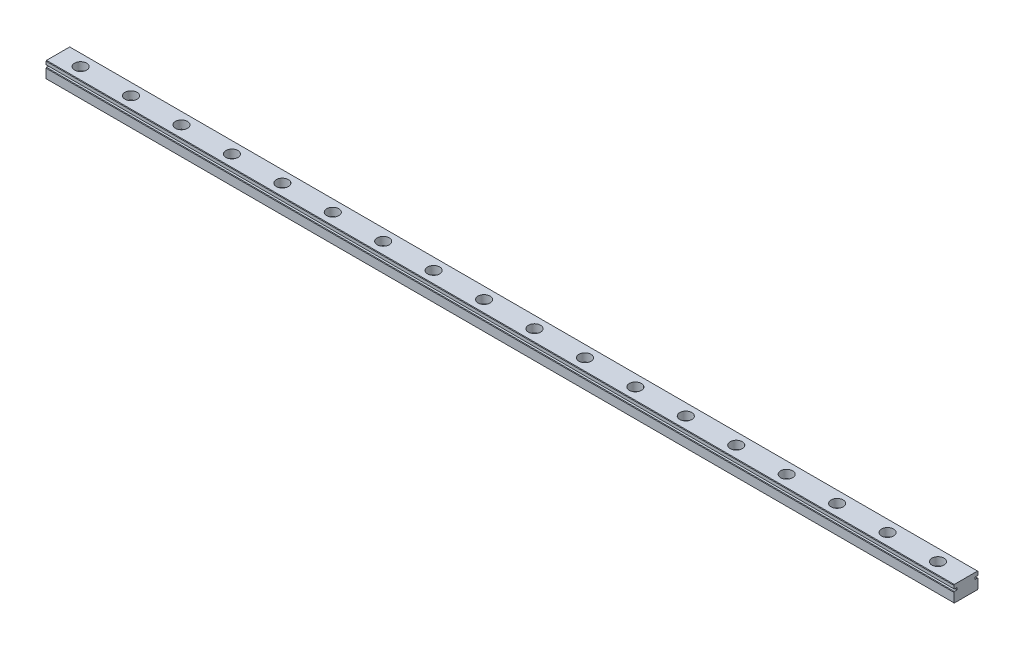
SolidWorks part; units mm, degrees
ref_plane "Plan de face" through (0, 0, 0) normal (0, 0, 1) x (1, 0, 0)
ref_plane "Plan de dessus" through (0, 0, 0) normal (0, 1, 0) x (1, 0, 0)
ref_plane "Plan de droite" through (0, 0, 0) normal (1, 0, 0) x (0, 0, -1)
sketch "Esquisse1" plane through (0, 0, 0) normal (1, 0, 0) x (0, 0, -1)
  line L0 (6, 5) -> (6, 0)
  line L1 (6, 8) -> (0, 8)
  line L2 (6, 8) -> (6, 6)
  line L3 (6, 0) -> (0, 0)
  line L5 (6, 6) -> (4.4, 6)
  line L7 (6, 5) -> (4.4, 5)
  line L8 (4.4, 6) -> (4.4, 5)
  line L9 (0, 8) -> (0, 0)
  dimension "D1" = 6
  dimension "D2" = 8
  dimension "D3" = 2
  dimension "D4" = 5
  dimension "D5" = 4.4
extrude "Boss.-Extru.1" add sketch "Esquisse1" along normal blind 450
chamfer "Chanfrein1" distance 0.25 angle 45 4 edges at (225, 6, -6) (225, 0, -6) (225, 5, -6) (225, 8, -6)
mirror "Symétrie1" about plane through (0, 0, 0) normal (0, 0, 1) of "Chanfrein1", "Boss.-Extru.1"
sketch "Esquisse2" plane through (0, 8, 0) normal (0, 1, 0) x (1, 0, 0)
  line L0 (0, 0) -> (11.1535, 0) construction
  line L1 (0, 5.75) -> (0, -5.75) construction
  circle A0 centre (11.1535, 0) radius 3
  dimension "D1" = 6
extrude "Enlèv. mat.-Extru.1" cut sketch "Esquisse2" against normal blind 4
sketch "Esquisse3" plane through (0, 4, 0) normal (0, 1, 0) x (1, 0, 0)
  circle A0 centre (11.1535, 0) radius 1.65
  dimension "D1" = 3.3
extrude "Enlèv. mat.-Extru.2" cut sketch "Esquisse3" against normal through all
pattern_linear "Répétition linéaire1" count 18 spacing 25 along (1, 0, 0) of "Enlèv. mat.-Extru.1", "Enlèv. mat.-Extru.2"
